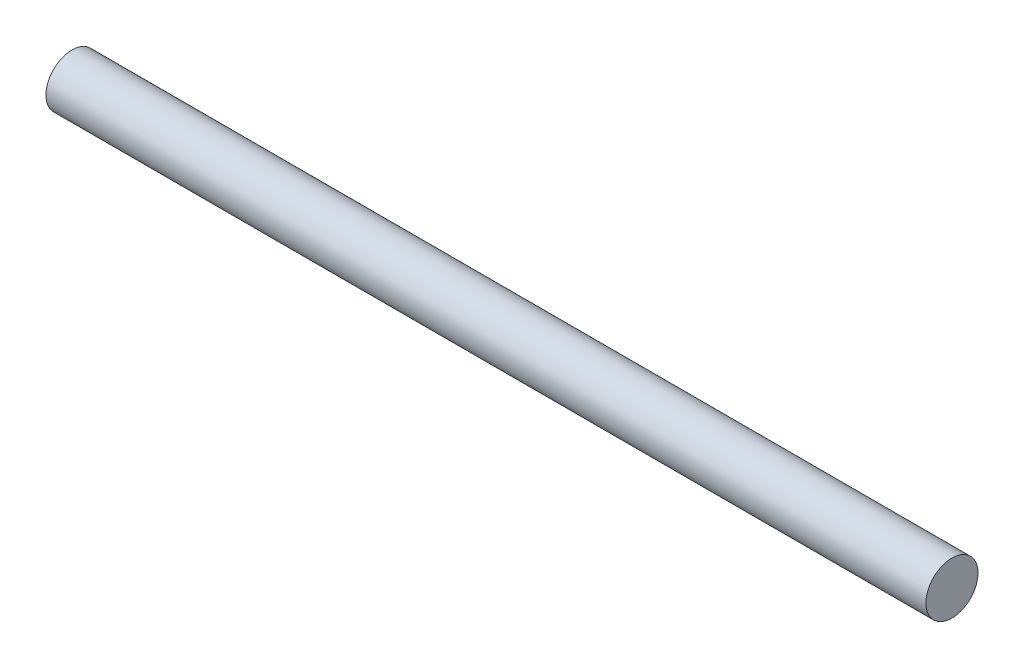
SolidWorks part; units mm, degrees
ref_plane "Front Plane" through (0, 0, 0) normal (0, 0, 1) x (1, 0, 0)
ref_plane "Top Plane" through (0, 0, 0) normal (0, 1, 0) x (1, 0, 0)
ref_plane "Right Plane" through (0, 0, 0) normal (1, 0, 0) x (0, 0, -1)
sketch "Sketch1" plane through (0, 0, 0) normal (1, 0, 0) x (0, 0, -1)
  circle A0 centre (0, 0) radius 2.25
  dimension "D1" = 4.5
extrude "Boss-Extrude1" add sketch "Sketch1" along normal blind 76
